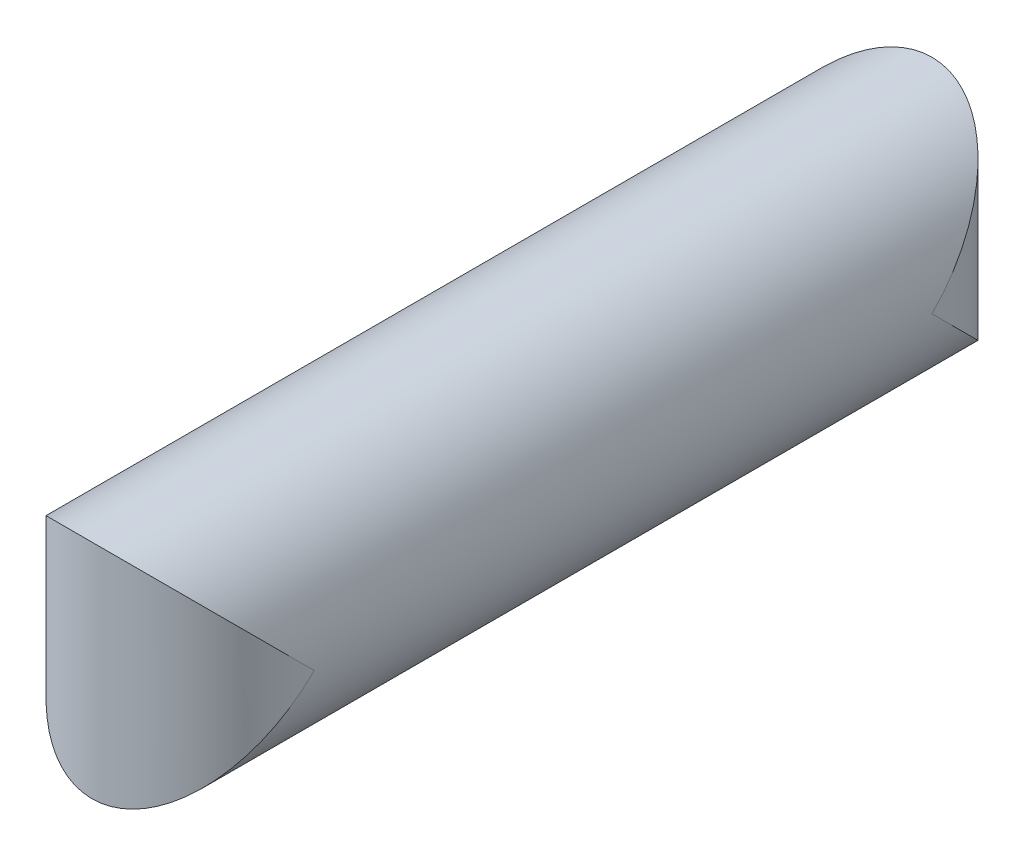
SolidWorks part; units mm, degrees
ref_plane "Front Plane" through (0, 0, 0) normal (0, 0, 1) x (1, 0, 0)
ref_plane "Top Plane" through (0, 0, 0) normal (0, 1, 0) x (1, 0, 0)
ref_plane "Right Plane" through (0, 0, 0) normal (1, 0, 0) x (0, 0, -1)
sketch "Sketch1" plane through (0, 0, 0) normal (0, 0, 1) x (1, 0, 0)
  circle A0 centre (0, 0) radius 3.9688
  dimension "D1" = 7.9375
extrude "Boss-Extrude1" add sketch "Sketch1" along normal blind 30
sketch "Sketch2" plane through (0, 0, 0) normal (0, 1, 0) x (1, 0, 0)
  line L0 (-3.9688, -30) -> (3.9688, -30) construction
  line L1 (0, -30) -> (0, -27) construction
  line L3 (-3.9687, -24) -> (3.9688, -24)
  line L4 (-3.9687, -24) -> (-3.9687, -30)
  line L5 (-3.9687, -30) -> (3.9688, -30)
  line L6 (3.9688, -24) -> (3.9688, -30)
  line L7 (-3.9687, -24) -> (3.9688, -30) construction
  line L8 (-3.9687, -30) -> (3.9688, -24) construction
  circle A0 centre (0, -27) radius 1.5
  arc A1 (-3.9687, -26.0312) -> (3.9688, -26.0312) centre (0, -26.0312) ccw
  dimension "D2" = 3
  dimension "D1" = 3
extrude "Cut-Extrude1" cut sketch "Sketch2" against normal through all and the other way through all contours A1 L4 L5 | A1 L5 L6
sketch "Sketch3" plane through (0, 0, 0) normal (0, 1, 0) x (1, 0, 0)
  line L1 (3.9688, -26.0312) -> (3.9688, 0) construction
  line L2 (3.9688, -3.9687) -> (-3.9688, -3.9687)
  line L3 (-3.9688, 0) -> (-3.9688, -26.0312) construction
  line L4 (-3.9688, -3.9687) -> (-3.9688, 0)
  line L5 (3.9688, -3.9687) -> (3.9688, 0)
  line L6 (3.9688, 0) -> (-3.9688, 0)
  arc A0 (3.9688, -3.9687) -> (-3.9688, -3.9687) centre (0, -3.9687) ccw
extrude "Cut-Extrude2" cut sketch "Sketch3" against normal through all and the other way through all
